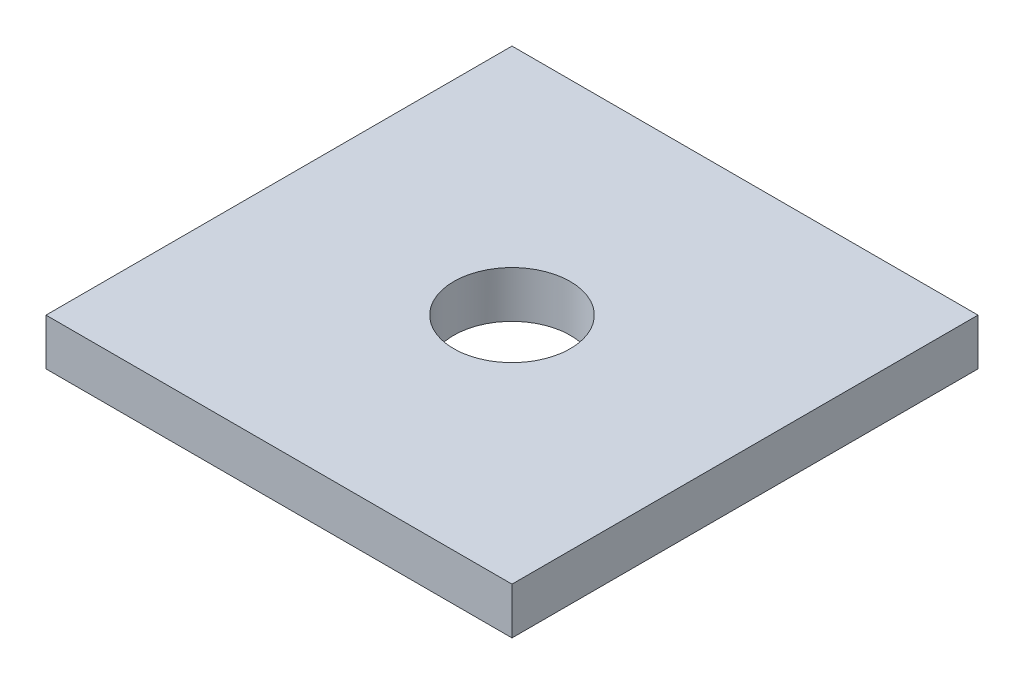
SolidWorks part; units mm, degrees
ref_plane "Front Plane" through (0, 0, 0) normal (0, 0, 1) x (1, 0, 0)
ref_plane "Top Plane" through (0, 0, 0) normal (0, 1, 0) x (1, 0, 0)
ref_plane "Right Plane" through (0, 0, 0) normal (1, 0, 0) x (0, 0, -1)
sketch "Sketch1" plane through (0, 0, 0) normal (0, 1, 0) x (1, 0, 0)
  line L1 (-20, 20) -> (20, 20)
  line L2 (-20, 20) -> (-20, -20)
  line L3 (-20, -20) -> (20, -20)
  line L4 (20, 20) -> (20, -20)
  line L5 (-20, 20) -> (20, -20) construction
  line L6 (-20, -20) -> (20, 20) construction
  point P0 (0, 0)
  dimension "D1" = 40
  dimension "D2" = 40
extrude "Boss-Extrude1" add sketch "Sketch1" along normal blind 4
sketch "Sketch2" plane through (0, 0, 0) normal (0, -1, 0) x (1, 0, 0)
  circle A0 centre (0, 0) radius 5
  dimension "D1" = 10
extrude "Cut-Extrude1" cut sketch "Sketch2" against normal blind 10
